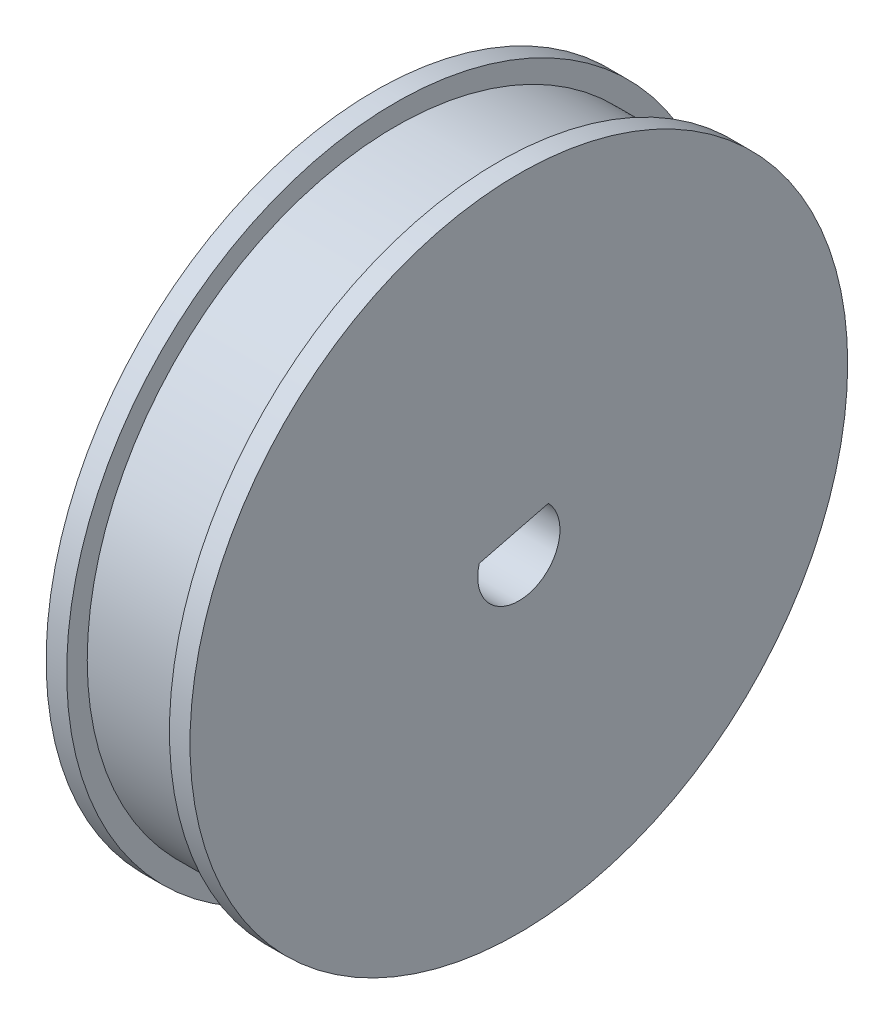
SolidWorks part; units mm, degrees
ref_plane "Front Plane" through (0, 0, 0) normal (0, 0, 1) x (1, 0, 0)
ref_plane "Top Plane" through (0, 0, 0) normal (0, 1, 0) x (1, 0, 0)
ref_plane "Right Plane" through (0, 0, 0) normal (1, 0, 0) x (0, 0, -1)
sketch "Sketch1" plane through (0, 0, 0) normal (1, 0, 0) x (0, 0, -1)
  line L0 (-1.9239, 0.5463) -> (1.4351, 1.393)
  circle A0 centre (0, 0) radius 16
  arc A1 (-1.9239, 0.5463) -> (1.4351, 1.393) centre (0, 0) ccw
  dimension "D1" = 1
  dimension "D2" = 32
  dimension "D3" = 2
extrude "Boss-Extrude1" add sketch "Sketch1" along normal blind 7
ref_plane "Plane1" through (6, 0, 0) normal (1, 0, 0) x (0, 0, -1)
sketch "Sketch3" plane through (6, 0, 0) normal (1, 0, 0) x (0, 0, -1)
  circle A0 centre (0, 0) radius 16 construction
  circle A1 centre (0, 0) radius 16
  circle A2 centre (0, 0) radius 15
extrude "Cut-Extrude1" cut sketch "Sketch3" against normal blind 5
